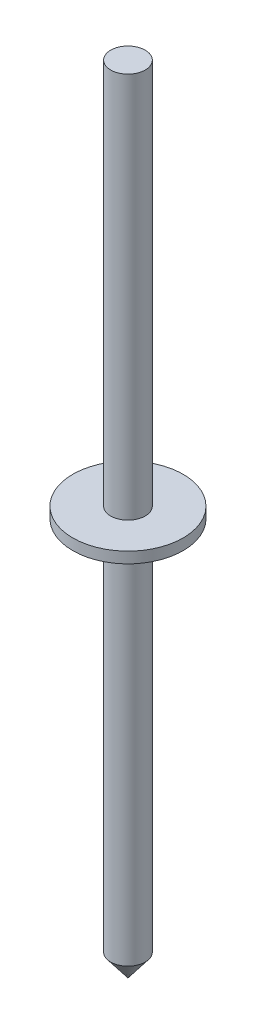
SolidWorks part; units mm, degrees
ref_plane "Front Plane" through (0, 0, 0) normal (0, 0, 1) x (1, 0, 0)
ref_plane "Top Plane" through (0, 0, 0) normal (0, 1, 0) x (1, 0, 0)
ref_plane "Right Plane" through (0, 0, 0) normal (1, 0, 0) x (0, 0, -1)
sketch "Sketch1" plane through (0, 0, 0) normal (0, 1, 0) x (1, 0, 0)
  circle A0 centre (0, 0) radius 12.7
  circle A1 centre (0, 0) radius 3.9688
  dimension "D1" = 7.9375
  dimension "D2" = 25.4
extrude "Boss-Extrude1" add sketch "Sketch1" along normal blind 2.54
sketch "Sketch2" plane through (0, 2.54, 0) normal (0, 1, 0) x (1, 0, 0)
  circle A0 centre (0, 0) radius 3.9688
extrude "Boss-Extrude2" add sketch "Sketch2" against normal blind 177.8 from offset 88.9
sketch "Sketch3" plane through (0, 0, 0) normal (1, 0, 0) x (0, 0, -1)
  line L0 (0, -87.9206) -> (0, -81.186) construction
  line L1 (0, -86.36) -> (-3.9688, -86.36)
  line L2 (-3.9688, -86.36) -> (3.9688, -86.36) construction
  line L3 (-3.9688, -86.36) -> (0, -91.5172)
  line L4 (0, -91.5172) -> (0, -86.36)
revolve "Revolve1" add sketch "Sketch3" angle 360 about L0
